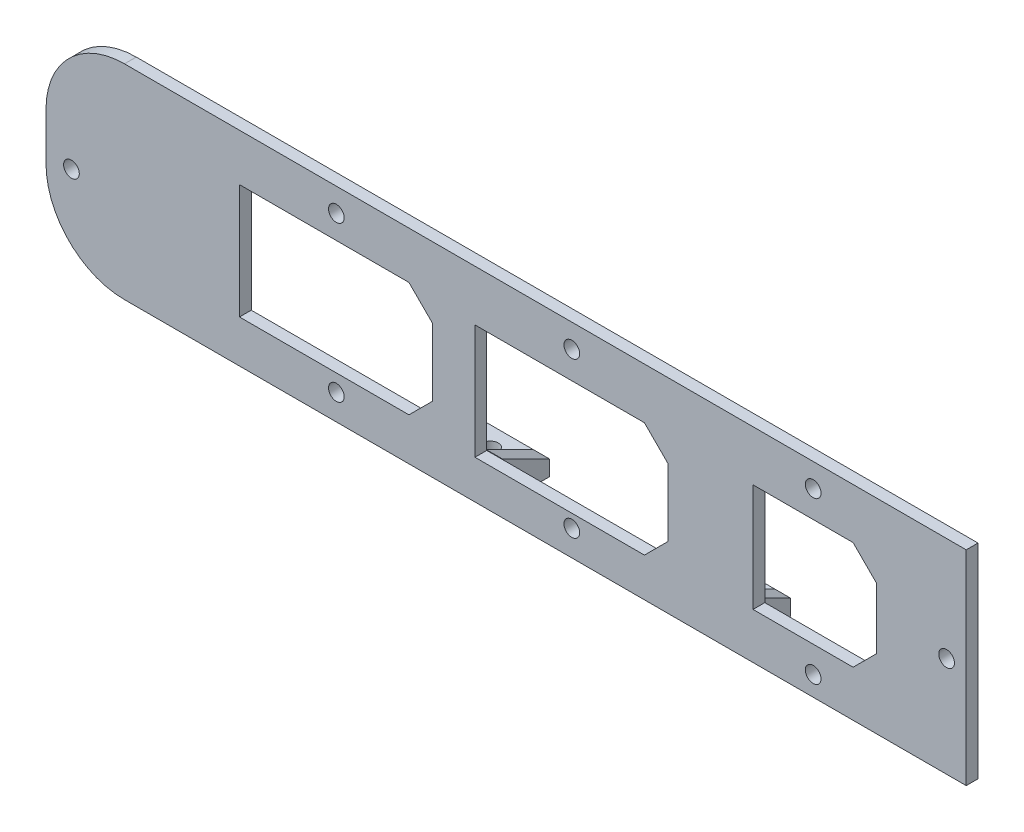
SolidWorks part; units mm, degrees
ref_plane "Front Plane" through (0, 0, 0) normal (0, 0, 1) x (1, 0, 0)
ref_plane "Top Plane" through (0, 0, 0) normal (0, 1, 0) x (1, 0, 0)
ref_plane "Right Plane" through (0, 0, 0) normal (1, 0, 0) x (0, 0, -1)
sketch "Sketch1" plane through (0, 0, 0) normal (0, 0, 1) x (1, 0, 0)
  line L1 (-114.75, -24.5) -> (114.75, -24.5)
  line L2 (-114.75, -24.5) -> (-114.75, 24.5)
  line L3 (-114.75, 24.5) -> (114.75, 24.5)
  line L4 (114.75, -24.5) -> (114.75, 24.5)
  line L5 (-114.75, -24.5) -> (114.75, 24.5) construction
  line L6 (-114.75, 24.5) -> (114.75, -24.5) construction
  point P0 (0, 0)
extrude "Boss-Extrude1" add sketch "Sketch1" along normal blind 3 contours L2 L1 L4 L3
sketch "Sketch2" plane through (0, 0, 3) normal (0, 0, 1) x (1, 0, 0)
  line L2 (-114.75, 24.5) -> (114.75, 24.5) construction
  circle A0 centre (111.75, 4) radius 2
  circle A1 centre (-111.25, 0.5) radius 2
  circle A2 centre (-43.75, 24.5) radius 2
  circle A3 centre (16.25, 24.5) radius 2
  circle A4 centre (77.75, 24.5) radius 2
sketch "Sketch3" plane through (0, 24.5, 0) normal (0, 1, 0) x (1, 0, 0)
  line L1 (-114.75, 0) -> (114.75, 0)
  line L2 (-114.75, 0) -> (-114.75, -3)
  line L3 (-114.75, -3) -> (114.75, -3)
  line L4 (114.75, 0) -> (114.75, -3)
extrude "Boss-Extrude2" add sketch "Sketch3" along normal blind 6
extrude "Cut-Extrude1" cut sketch "Sketch2" against normal blind 31.956
sketch "Sketch4" plane through (0, 0, 3) normal (0, 0, 1) x (1, 0, 0)
  line L24 (62.4249, 17.6814) -> (62.4249, -9.8186)
  line L25 (62.4249, -9.8186) -> (87.9249, -9.8186)
  line L38 (62.4249, 17.6814) -> (87.9249, 17.6814)
  line L52 (87.9249, 17.6814) -> (93.9249, 11.6814)
  line L53 (93.9249, -3.8186) -> (87.9249, -9.8186)
  line L54 (93.9249, -3.8186) -> (93.9249, 11.6814)
  line L57 (-19.25, 12.5) -> (-25.25, 18.5)
  line L60 (-25.25, -10.71) -> (-19.25, -4.71)
  line L61 (-19.25, 12.5) -> (-19.25, -4.71)
  line L68 (34.7504, -11.664) -> (40.7504, -5.664)
  line L69 (40.7504, -5.664) -> (40.7504, 11.546)
  line L70 (34.7504, 17.546) -> (40.7504, 11.546)
  line L71 (-8.4296, 17.546) -> (34.7504, 17.546)
  line L72 (-8.4296, 17.546) -> (-8.4296, -11.664)
  line L73 (-8.4296, -11.664) -> (34.7504, -11.664)
  line L75 (-68.43, 18.5) -> (-68.43, -10.71)
  line L76 (-68.43, -10.71) -> (-25.25, -10.71)
  line L77 (-68.43, 18.5) -> (-25.25, 18.5)
  circle A0 centre (-43.75, -15) radius 2
  circle A1 centre (16.25, -15) radius 2
  circle A2 centre (77.75, -16.5) radius 2
  point P3 (-43.75, 11.752)
extrude "Cut-Extrude2" cut sketch "Sketch4" against normal blind 31.956
sketch "Sketch5" plane through (0, 0, 3) normal (0, 0, 1) x (1, 0, 0)
  line L0 (-111.25, -5.5) -> (-67.25, -24.5)
  line L1 (-114.75, -24.5) -> (114.75, -24.5) construction
  line L2 (-111.25, 6.5) -> (-67.25, 30.5)
  line L3 (-114.75, 30.5) -> (114.75, 30.5) construction
  line L4 (-67.25, -24.5) -> (-114.75, -24.5)
  line L5 (-114.75, -24.5) -> (-114.75, -4.3734)
  line L6 (-114.75, -24.5) -> (-114.75, 30.5) construction
  line L7 (-114.75, 30.5) -> (-67.25, 30.5)
  line L8 (-114.75, 30.5) -> (-114.75, 5.3734)
  circle A1 centre (-111.25, 0.5) radius 6
  line M13 (-114.75, 30.5) -> (-114.75, -24.5)
extrude "Boss-Extrude3" add sketch "Sketch5" against normal blind 3 contours A1 M13
sketch "Sketch10" plane through (0, 0, 0) normal (0, 0, -1) x (-1, 0, 0)
  line L0 (-77.75, 24.5) -> (-77.75, -21.5375)
  line L1 (-77.75, -21.5375) -> (-114.75, -21.5375)
  line L2 (-114.75, -24.5) -> (-114.75, 30.5) construction
  line L4 (-114.75, -21.5375) -> (114.75, -21.5375)
  line L5 (-114.75, -21.5375) -> (-114.75, -24.5)
  line L6 (-114.75, -24.5) -> (114.75, -24.5)
  line L7 (114.75, -21.5375) -> (114.75, -24.5)
extrude "Cut-Extrude5" cut sketch "Sketch10" against normal blind 11.382 contours L4 L7 L6 L5
sketch "Sketch12" plane through (0, 0, 0) normal (0, 0, -1) x (-1, 0, 0)
  line L3 (13.75, -21.5375) -> (-47, -21.5375)
  line L4 (-114.75, -21.5375) -> (114.75, -21.5375) construction
  line L5 (-16.25, -21.5375) -> (-77.75, -21.5375)
  line L19 (20.5, -21.5375) -> (8.5, -21.5375)
  line L20 (8.5, -17.5375) -> (8.5, -21.5375)
  line L21 (20.5, -17.5375) -> (8.5, -17.5375)
  line L22 (-53, -17.5375) -> (-41, -17.5375)
  line L23 (-53, -17.5375) -> (-53, -21.5375)
  line L24 (-53, -21.5375) -> (-41, -21.5375)
  line L25 (-41, -17.5375) -> (-41, -21.5375)
  line L26 (20.5, -17.5375) -> (20.5, -21.5375)
  line M56 (-114.75, -21.5375) -> (114.75, -21.5375)
extrude "Boss-Extrude4" add sketch "Sketch12" along normal blind 12 contours L25 L22 L23 L5 M56 | L26 L21 L20 M56
sketch "Sketch13" plane through (0, -17.5375, 0) normal (0, 1, 0) x (1, 0, 0)
  circle A3 centre (-14.5, 7) radius 2
  circle A4 centre (47, 7) radius 2
extrude "Cut-Extrude7" cut sketch "Sketch13" against normal blind 15
sketch "Sketch14" plane through (53, 0, 0) normal (1, 0, 0) x (0, 0, -1)
  line L0 (0, -17.5375) -> (0, -11.5375)
  line L4 (0, -11.5375) -> (12, -17.5375)
  line L5 (12, -17.5375) -> (0, -17.5375) construction
  line L6 (12, -17.5375) -> (12, -21.5375)
  line L7 (12, -21.5375) -> (0, -21.5375) construction
  line L8 (12, -17.5375) -> (12, -21.5375) construction
  line L9 (12, -21.5375) -> (0, -21.5375)
  line L10 (0, -21.5375) -> (0, -17.5375)
extrude "Boss-Extrude5" add sketch "Sketch14" along normal blind 4
sketch "Sketch15" plane through (41, 0, 0) normal (-1, 0, 0) x (0, 0, 1)
  line L0 (0, -17.5375) -> (0, -11.5375)
  line L1 (0, -11.5375) -> (-12, -17.5375)
  line L2 (-12, -17.5375) -> (-12, -21.5375)
  line L3 (-12, -21.5375) -> (0, -21.5375)
  line L4 (0, -21.5375) -> (0, -17.5375)
extrude "Boss-Extrude6" add sketch "Sketch15" along normal blind 4
sketch "Sketch16" plane through (-8.5, 0, 0) normal (1, 0, 0) x (0, 0, -1)
  line L0 (0, -17.5375) -> (0, -11.5375)
  line L1 (0, -11.5375) -> (12, -17.5375)
  line L2 (12, -17.5375) -> (12, -21.5375)
  line L3 (12, -21.5375) -> (0, -21.5375)
  line L4 (0, -21.5375) -> (0, -17.5375)
extrude "Boss-Extrude7" add sketch "Sketch16" along normal blind 4
sketch "Sketch17" plane through (-20.5, 0, 0) normal (-1, 0, 0) x (0, 0, 1)
  line L0 (0, -17.5375) -> (0, -11.5375)
  line L1 (0, -11.5375) -> (-12, -17.5375)
  line L2 (-12, -17.5375) -> (-12, -21.5375)
  line L3 (-12, -21.5375) -> (0, -21.5375) construction
  line L4 (-12, -17.5375) -> (-12, -21.5375) construction
  line L5 (-12, -21.5375) -> (0, -21.5375)
  line L6 (0, -21.5375) -> (0, -17.5375)
extrude "Boss-Extrude8" add sketch "Sketch17" along normal blind 4
sketch "Sketch19" plane through (-114.75, 0, 0) normal (-1, 0, 0) x (0, 0, 1)
  line L1 (0, 30.5) -> (3, 30.5)
  line L2 (0, 30.5) -> (0, -21.5375)
  line L3 (0, -21.5375) -> (3, -21.5375)
  line L4 (3, 30.5) -> (3, -21.5375)
extrude "Boss-Extrude9" add sketch "Sketch19" along normal blind 2.984
sketch "Sketch20" plane through (0, 0, 3) normal (0, 0, 1) x (1, 0, 0)
  line L0 (-97.734, 30.5) -> (-117.734, 30.5)
  line L1 (-97.734, 30.5) -> (114.75, 30.5)
  line L2 (-117.734, 10.5) -> (-117.734, -1.5375)
  line L3 (-97.734, -21.5375) -> (114.75, -21.5375)
  line L4 (114.75, 30.5) -> (114.75, -21.5375)
  line L5 (-117.734, 30.5) -> (-117.734, -21.5375)
  line L6 (-117.734, -21.5375) -> (-97.734, -21.5375)
  arc A0 (-117.734, 10.5) -> (-97.734, 30.5) centre (-97.734, 10.5) cw
  arc A1 (-97.734, -21.5375) -> (-117.734, -1.5375) centre (-97.734, -1.5375) cw
  point P8 (-117.734, 30.5)
  line M7 (-117.734, 30.5) -> (-117.734, -21.5375)
  line M8 (-117.734, -21.5375) -> (114.75, -21.5375)
  line M10 (114.75, 30.5) -> (-117.734, 30.5)
  dimension "D1" = 20
  dimension "D2" = 20
extrude "Cut-Extrude8" cut sketch "Sketch20" against normal blind 20.764 contours A0 M7 M10 | A1 M8 M7
ref_plane "Plane1" through (114.75, -21.5375, 3) normal (0, 1, 0) x (1, 0, 0)
sketch "Sketch23" plane through (114.75, 0, 0) normal (1, 0, 0) x (0, 0, -1)
  line L1 (-3, 30.5) -> (0, 30.5)
  line L2 (-3, 30.5) -> (-3, -21.5375)
  line L3 (-3, -21.5375) -> (0, -21.5375)
  line L4 (0, 30.5) -> (0, -21.5375)
extrude "Boss-Extrude10" add sketch "Sketch23" along normal blind 2
sketch "Sketch24" plane through (0, -21.5375, 0) normal (0, -1, 0) x (1, 0, 0)
  line L0 (-4.5, 0) -> (-4.5, -12) construction
  line L1 (-24.5, 0) -> (-4.5, 0)
  line L2 (-24.5, 0) -> (-24.5, -3)
  line L3 (-24.5, -3) -> (-4.5, -3)
  line L4 (-4.5, 0) -> (-4.5, -3)
  line L5 (57, 0) -> (57, -12) construction
  line L6 (37, 0) -> (57, 0)
  line L7 (37, 0) -> (37, -3)
  line L8 (37, -3) -> (57, -3)
  line L9 (57, 0) -> (57, -3)
extrude "Cut-Extrude9" cut sketch "Sketch24" against normal blind 3
sketch "Sketch25" plane through (0, 0, 3) normal (0, 0, 1) x (1, 0, 0)
  line L0 (-117.734, 10.5) -> (-117.734, -1.5375)
  arc A0 (-97.734, 30.5) -> (-117.734, 10.5) centre (-97.734, 10.5) ccw
  arc A1 (-117.734, -1.5375) -> (-97.734, -21.5375) centre (-97.734, -1.5375) ccw
